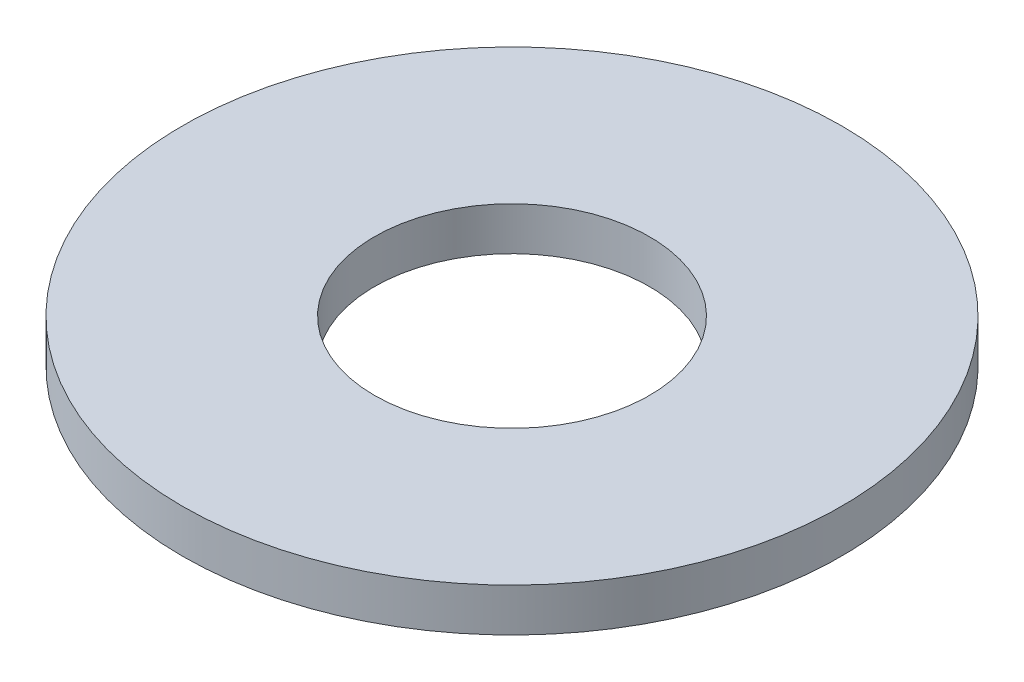
SolidWorks part; units mm, degrees
ref_plane "Front Plane" through (0, 0, 0) normal (0, 0, 1) x (1, 0, 0)
ref_plane "Top Plane" through (0, 0, 0) normal (0, 1, 0) x (1, 0, 0)
ref_plane "Right Plane" through (0, 0, 0) normal (1, 0, 0) x (0, 0, -1)
sketch "Sketch1" plane through (0, 0, 0) normal (0, 1, 0) x (1, 0, 0)
  circle A0 centre (0, 0) radius 38.1
  circle A1 centre (0, 0) radius 15.9
  dimension "D1" = 76.2
  dimension "D2" = 31.8
extrude "Boss-Extrude1" add sketch "Sketch1" along normal blind 5
